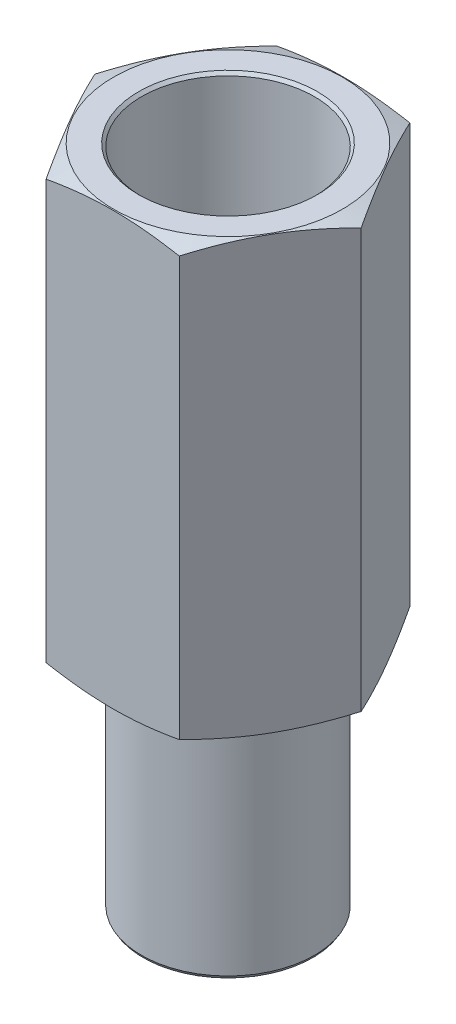
SolidWorks part; units mm, degrees
material "黄铜"
ref_plane "前视基准面" through (0, 0, 0) normal (0, 0, 1) x (1, 0, 0)
ref_plane "上视基准面" through (0, 0, 0) normal (0, 1, 0) x (1, 0, 0)
ref_plane "右视基准面" through (0, 0, 0) normal (1, 0, 0) x (0, 0, -1)
other "Configuration Table"
sketch "草图1" plane through (0, 0, 0) normal (0, 1, 0) x (1, 0, 0)
  line L1 (2.3094, 4) -> (-2.3094, 4)
  line L2 (-2.3094, 4) -> (-4.6188, 0)
  line L3 (-4.6188, 0) -> (-2.3094, -4)
  line L4 (-2.3094, -4) -> (2.3094, -4)
  line L5 (2.3094, -4) -> (4.6188, 0)
  line L6 (4.6188, 0) -> (2.3094, 4)
  circle A0 centre (0, 0) radius 4 construction
  dimension "D" = 8
extrude "凸台-拉伸1" add sketch "草图1" along normal blind 15
sketch "草图2" plane through (0, 0, 0) normal (0, -1, 0) x (1, 0, 0)
  circle A0 centre (0, 0) radius 3
  dimension "M" = 6
extrude "凸台-拉伸2" add sketch "草图2" along normal blind 8
sketch "草图3" plane through (0, 15, 0) normal (0, 1, 0) x (1, 0, 0)
  circle A0 centre (0, 0) radius 3
  dimension "M" = 6
extrude "切除-拉伸1" cut sketch "草图3" against normal offset from surface (14 mm away) 1 up to face at (0, 0, -3)
ref_axis "基准轴1" through (0, -9.15, 0) along (0, 1, 0)
sketch "草图4" plane through (0, 0, 0) normal (0, 0, 1) x (1, 0, 0)
  line L4 (-4.6188, 0.2359) -> (-4.6188, 0)
  line L6 (-4.6188, 0) -> (-3.9708, 0)
  line L7 (-4.6188, 0) -> (-2.3094, 0) construction
  line L8 (-3.9708, 0) -> (-4.6188, 0.2359)
  line L9 (-4.6188, 15) -> (-4.6188, 14.7641)
  line L10 (-4.6188, 15) -> (-4.6188, 0) construction
  line L11 (-4.6188, 14.7641) -> (-3.9708, 15)
  line L12 (-4.6188, 15) -> (-2.3094, 15) construction
  line L13 (-3.9708, 15) -> (-4.6188, 15)
  dimension "D1" = 20
  dimension "D2" = 0.648
  dimension "D3" = 20
revolve "切除-旋转1" cut sketch "草图4" angle 360 about axis through (0, -9.15, 0) along (0, 1, 0)
chamfer "倒角1" distance 0.1 angle 30 1 edges at (0, -8, -3)
chamfer "倒角2" distance 0.1 angle 45 1 edges at (0, 15, 3)
equation "\"D2@草图4\"=0.2*(1.155*\"D@草图1\"-\"M@草图2\")"
